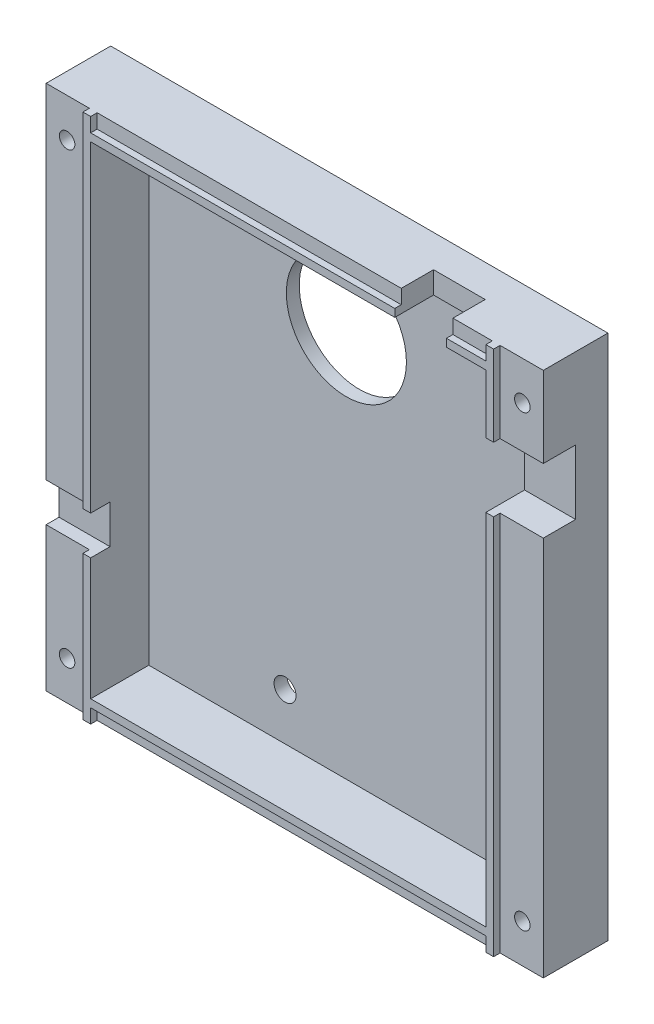
SolidWorks part; units mm, degrees
ref_plane "Front Plane" through (0, 0, 0) normal (1, 0, 0) x (0, 1, 0)
ref_plane "Top Plane" through (0, 0, 0) normal (0, 0, 1) x (0, 1, 0)
ref_plane "Right Plane" through (0, 0, 0) normal (0, 1, 0) x (-1, 0, 0)
sketch "Sketch1" plane through (0, 0, 0) normal (0, 0, 1) x (0, 1, 0)
  line L1 (0, 0) -> (81.5, 0)
  line L2 (0, 0) -> (0, -77)
  line L3 (0, -77) -> (81.5, -77)
  line L4 (81.5, 0) -> (81.5, -77)
extrude "Boss-Extrude1" add sketch "Sketch1" along normal blind 2
sketch "Sketch2" plane through (0, 0, 0) normal (0, 0, 1) x (0, 1, 0)
  line L0 (81.5, -77) -> (81.5, 0) construction
  line L1 (0, 0) -> (81.5, 0)
  line L2 (0, 0) -> (0, -6.7)
  line L3 (0, -6.7) -> (81.5, -6.7)
  line L4 (81.5, 0) -> (81.5, -6.7)
extrude "Boss-Extrude2" add sketch "Sketch2" along normal blind 8
sketch "Sketch3" plane through (0, 0, 0) normal (0, 0, 1) x (0, 1, 0)
  line L0 (0, -6.7) -> (81.5, -6.7) construction
  line L1 (0, 0) -> (22.3, 0)
  line L2 (0, 0) -> (0, -6.7)
  line L3 (0, -6.7) -> (22.3, -6.7)
  line L4 (22.3, 0) -> (22.3, -6.7)
extrude "Boss-Extrude3" add sketch "Sketch3" along normal blind 10
sketch "Sketch4" plane through (0, 0, 0) normal (0, 0, 1) x (0, 1, 0)
  line L0 (81.5, 0) -> (22.3, 0) construction
  line L1 (28.3, 0) -> (81.5, 0)
  line L2 (28.3, 0) -> (28.3, -6.7)
  line L3 (28.3, -6.7) -> (81.5, -6.7)
  line L4 (81.5, 0) -> (81.5, -6.7)
extrude "Boss-Extrude4" add sketch "Sketch4" along normal blind 10
sketch "Sketch5" plane through (0, 0, 0) normal (0, 0, 1) x (0, 1, 0)
  line L0 (81.5, -77) -> (81.5, -6.7) construction
  line L1 (0, -6.7) -> (81.5, -6.7)
  line L2 (0, -6.7) -> (0, -7.9)
  line L3 (0, -7.9) -> (81.5, -7.9)
  line L4 (81.5, -6.7) -> (81.5, -7.9)
extrude "Boss-Extrude5" add sketch "Sketch5" along normal blind 8
sketch "Sketch6" plane through (0, 0, 0) normal (0, 0, 1) x (0, 1, 0)
  line L0 (0, -7.9) -> (81.5, -7.9) construction
  line L1 (0, -6.7) -> (22.3, -6.7)
  line L2 (0, -6.7) -> (0, -7.9)
  line L3 (0, -7.9) -> (22.3, -7.9)
  line L4 (22.3, -6.7) -> (22.3, -7.9)
extrude "Boss-Extrude6" add sketch "Sketch6" along normal blind 11
sketch "Sketch7" plane through (0, 0, 0) normal (0, 0, 1) x (0, 1, 0)
  line L1 (28.3, -6.7) -> (81.5, -6.7)
  line L2 (28.3, -6.7) -> (28.3, -7.9)
  line L3 (28.3, -7.9) -> (81.5, -7.9)
  line L4 (81.5, -6.7) -> (81.5, -7.9)
extrude "Boss-Extrude7" add sketch "Sketch7" along normal blind 11
sketch "Sketch8" plane through (0, 0, 0) normal (0, 0, 1) x (0, 1, 0)
  line L0 (0, -7.9) -> (0, -77) construction
  line L1 (0, -70.3) -> (81.5, -70.3)
  line L2 (0, -70.3) -> (0, -77)
  line L3 (0, -77) -> (81.5, -77)
  line L4 (81.5, -70.3) -> (81.5, -77)
extrude "Boss-Extrude8" add sketch "Sketch8" along normal blind 5
sketch "Sketch9" plane through (0, 0, 0) normal (0, 0, 1) x (0, 1, 0)
  line L0 (0, -77) -> (81.5, -77) construction
  line L1 (0, -70.3) -> (59, -70.3)
  line L2 (0, -70.3) -> (0, -77)
  line L3 (0, -77) -> (59, -77)
  line L4 (59, -70.3) -> (59, -77)
extrude "Boss-Extrude9" add sketch "Sketch9" along normal blind 10
sketch "Sketch10" plane through (0, 0, 0) normal (0, 0, 1) x (0, 1, 0)
  line L0 (0, -70.3) -> (81.5, -70.3) construction
  line L1 (69, -70.3) -> (81.5, -70.3)
  line L2 (69, -70.3) -> (69, -77)
  line L3 (69, -77) -> (81.5, -77)
  line L4 (81.5, -70.3) -> (81.5, -77)
extrude "Boss-Extrude10" add sketch "Sketch10" along normal blind 10
sketch "Sketch11" plane through (0, 0, 0) normal (0, 0, 1) x (0, 1, 0)
  line L0 (0, -7.9) -> (0, -70.3) construction
  line L1 (0, -69.1) -> (81.5, -69.1)
  line L2 (0, -69.1) -> (0, -70.3)
  line L3 (0, -70.3) -> (81.5, -70.3)
  line L4 (81.5, -69.1) -> (81.5, -70.3)
extrude "Boss-Extrude11" add sketch "Sketch11" along normal blind 5
sketch "Sketch12" plane through (0, 0, 0) normal (0, 0, 1) x (0, 1, 0)
  line L1 (0, -69.1) -> (59, -69.1)
  line L2 (0, -69.1) -> (0, -70.3)
  line L3 (0, -70.3) -> (59, -70.3)
  line L4 (59, -69.1) -> (59, -70.3)
extrude "Boss-Extrude12" add sketch "Sketch12" along normal blind 11
sketch "Sketch13" plane through (0, 0, 0) normal (0, 0, 1) x (0, 1, 0)
  line L0 (0, -69.1) -> (81.5, -69.1) construction
  line L1 (69, -69.1) -> (81.5, -69.1)
  line L2 (69, -69.1) -> (69, -70.3)
  line L3 (69, -70.3) -> (81.5, -70.3)
  line L4 (81.5, -69.1) -> (81.5, -70.3)
extrude "Boss-Extrude13" add sketch "Sketch13" along normal blind 11
sketch "Sketch14" plane through (0, 0, 0) normal (0, 0, 1) x (0, 1, 0)
  line L0 (0, -70.3) -> (59, -70.3) construction
  line L1 (0, -6.7) -> (2.2, -6.7)
  line L2 (0, -6.7) -> (0, -70.3)
  line L3 (0, -70.3) -> (2.2, -70.3)
  line L4 (2.2, -6.7) -> (2.2, -70.3)
extrude "Boss-Extrude14" add sketch "Sketch14" along normal blind 10
sketch "Sketch15" plane through (0, 0, 0) normal (0, 0, 1) x (0, 1, 0)
  line L0 (0, -7.9) -> (22.3, -7.9) construction
  line L1 (2.2, -7.9) -> (3.4, -7.9)
  line L2 (2.2, -7.9) -> (2.2, -69.1)
  line L3 (2.2, -69.1) -> (3.4, -69.1)
  line L4 (3.4, -7.9) -> (3.4, -69.1)
  line L5 (2.2, -69.1) -> (81.5, -69.1) construction
extrude "Boss-Extrude15" add sketch "Sketch15" along normal blind 11
sketch "Sketch16" plane through (0, 0, 0) normal (0, 0, 1) x (0, 1, 0)
  line L0 (28.3, -6.7) -> (81.5, -6.7) construction
  line L1 (79.3, -6.7) -> (81.5, -6.7)
  line L2 (79.3, -6.7) -> (79.3, -70.3)
  line L3 (79.3, -70.3) -> (81.5, -70.3)
  line L4 (81.5, -6.7) -> (81.5, -70.3)
extrude "Boss-Extrude16" add sketch "Sketch16" along normal blind 5
sketch "Sketch17" plane through (0, 0, 0) normal (0, 0, 1) x (0, 1, 0)
  line L0 (28.3, -6.7) -> (81.5, -6.7) construction
  line L1 (79.3, -6.7) -> (81.5, -6.7)
  line L2 (79.3, -6.7) -> (79.3, -55)
  line L3 (79.3, -55) -> (81.5, -55)
  line L4 (81.5, -6.7) -> (81.5, -55)
  line L5 (81.5, -69.1) -> (81.5, -7.9) construction
extrude "Boss-Extrude17" add sketch "Sketch17" along normal blind 10
sketch "Sketch18" plane through (0, 0, 0) normal (0, 0, 1) x (0, 1, 0)
  line L0 (79.3, -69.1) -> (79.3, -7.9) construction
  line L1 (79.3, -63) -> (81.5, -63)
  line L2 (79.3, -63) -> (79.3, -70.3)
  line L3 (79.3, -70.3) -> (81.5, -70.3)
  line L4 (81.5, -63) -> (81.5, -70.3)
extrude "Boss-Extrude18" add sketch "Sketch18" along normal blind 10
sketch "Sketch19" plane through (0, 0, 0) normal (0, 0, 1) x (0, 1, 0)
  line L0 (28.3, -7.9) -> (81.5, -7.9) construction
  line L1 (78.1, -7.9) -> (79.3, -7.9)
  line L2 (78.1, -7.9) -> (78.1, -69.1)
  line L3 (78.1, -69.1) -> (79.3, -69.1)
  line L4 (79.3, -7.9) -> (79.3, -69.1)
extrude "Boss-Extrude19" add sketch "Sketch19" along normal blind 5
sketch "Sketch20" plane through (0, 0, 0) normal (0, 0, 1) x (0, 1, 0)
  line L0 (28.3, -7.9) -> (81.5, -7.9) construction
  line L1 (78.1, -7.9) -> (79.3, -7.9)
  line L2 (78.1, -7.9) -> (78.1, -55)
  line L3 (78.1, -55) -> (79.3, -55)
  line L4 (79.3, -7.9) -> (79.3, -55)
extrude "Boss-Extrude20" add sketch "Sketch20" along normal blind 11
sketch "Sketch21" plane through (0, 0, 0) normal (0, 0, 1) x (0, 1, 0)
  line L0 (78.1, -69.1) -> (78.1, -7.9) construction
  line L1 (78.1, -63) -> (79.3, -63)
  line L2 (78.1, -63) -> (78.1, -69.1)
  line L3 (78.1, -69.1) -> (79.3, -69.1)
  line L4 (79.3, -63) -> (79.3, -69.1)
extrude "Boss-Extrude21" add sketch "Sketch21" along normal blind 11
sketch "Sketch22" plane through (0, 0, 0) normal (0, 0, 1) x (0, 1, 0)
  circle A0 centre (10.7, -29) radius 1.7
extrude "Cut-Extrude1" cut sketch "Sketch22" along normal blind 17
sketch "Sketch23" plane through (0, 0, 0) normal (0, 0, 1) x (0, 1, 0)
  circle A0 centre (64, -38.5) radius 9.3
extrude "Cut-Extrude2" cut sketch "Sketch23" along normal blind 17
sketch "Sketch24" plane through (0, 0, 0) normal (0, 0, 1) x (0, 1, 0)
  circle A0 centre (6, -3.25) radius 1.2
extrude "Cut-Extrude3" cut sketch "Sketch24" along normal blind 17
sketch "Sketch25" plane through (0, 0, 0) normal (0, 0, 1) x (0, 1, 0)
  circle A0 centre (6, -3.25) radius 2
extrude "Cut-Extrude4" cut sketch "Sketch25" along normal blind 1
sketch "Sketch26" plane through (0, 0, 0) normal (0, 0, 1) x (0, 1, 0)
  circle A0 centre (75.5, -3.25) radius 1.2
extrude "Cut-Extrude5" cut sketch "Sketch26" along normal blind 17
sketch "Sketch27" plane through (0, 0, 0) normal (0, 0, 1) x (0, 1, 0)
  circle A0 centre (75.5, -3.25) radius 2
extrude "Cut-Extrude6" cut sketch "Sketch27" along normal blind 1
sketch "Sketch28" plane through (0, 0, 0) normal (0, 0, 1) x (0, 1, 0)
  circle A0 centre (6, -73.75) radius 1.2
extrude "Cut-Extrude7" cut sketch "Sketch28" along normal blind 17
sketch "Sketch29" plane through (0, 0, 0) normal (0, 0, 1) x (0, 1, 0)
  circle A0 centre (6, -73.75) radius 2
extrude "Cut-Extrude8" cut sketch "Sketch29" along normal blind 1
sketch "Sketch30" plane through (0, 0, 0) normal (0, 0, 1) x (0, 1, 0)
  circle A0 centre (75.5, -73.75) radius 1.2
extrude "Cut-Extrude9" cut sketch "Sketch30" along normal blind 17
sketch "Sketch31" plane through (0, 0, 0) normal (0, 0, 1) x (0, 1, 0)
  circle A0 centre (75.5, -73.75) radius 2
extrude "Cut-Extrude10" cut sketch "Sketch31" along normal blind 1
